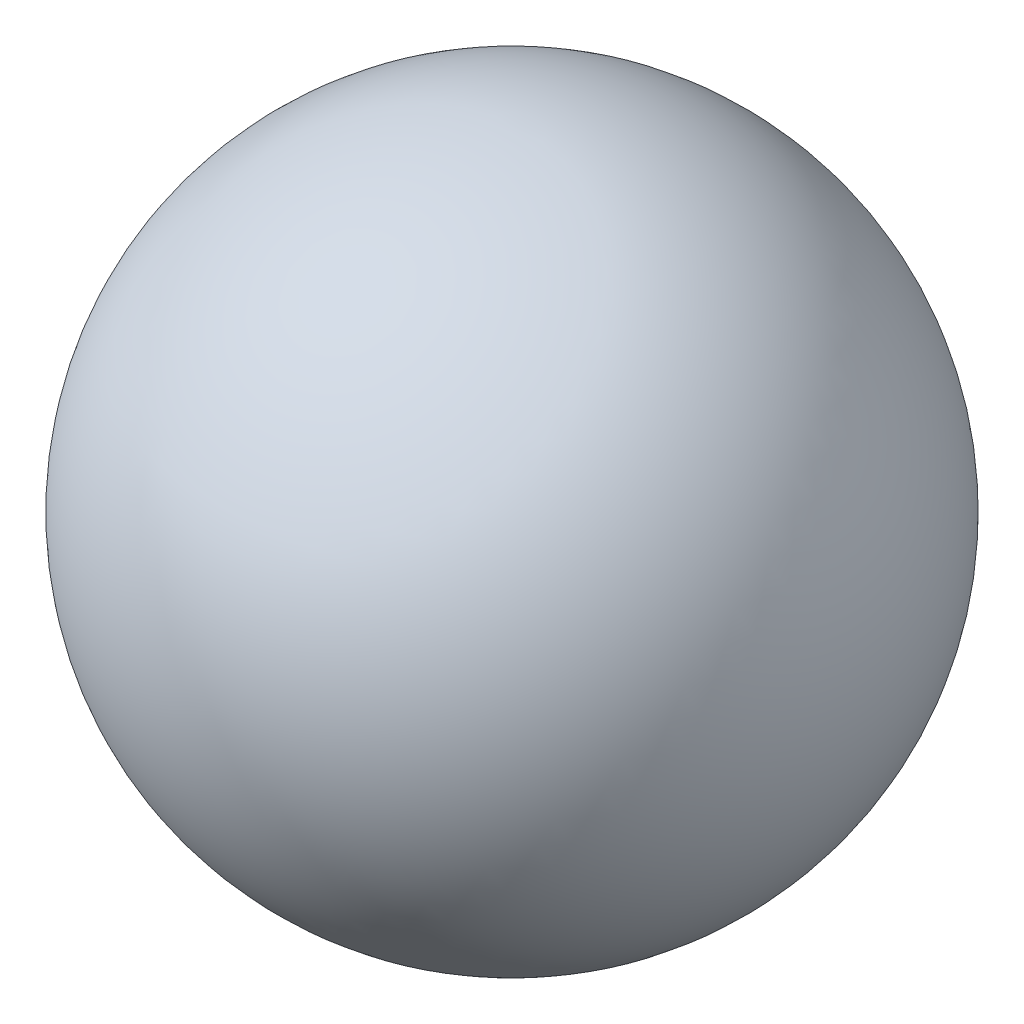
SolidWorks part; units mm, degrees
ref_plane "Front Plane" through (0, 0, 0) normal (0, 0, 1) x (1, 0, 0)
ref_plane "Top Plane" through (0, 0, 0) normal (0, 1, 0) x (1, 0, 0)
ref_plane "Right Plane" through (0, 0, 0) normal (1, 0, 0) x (0, 0, -1)
sketch "Sketch1" plane through (0, 0, 0) normal (0, 0, 1) x (1, 0, 0)
  line L0 (0, -18) -> (0, 18)
  arc A0 (0, -18) -> (0, 18) centre (0, 0) ccw
  dimension "D1" = 36
revolve "Revolve1" add sketch "Sketch1" angle 360 about L0
